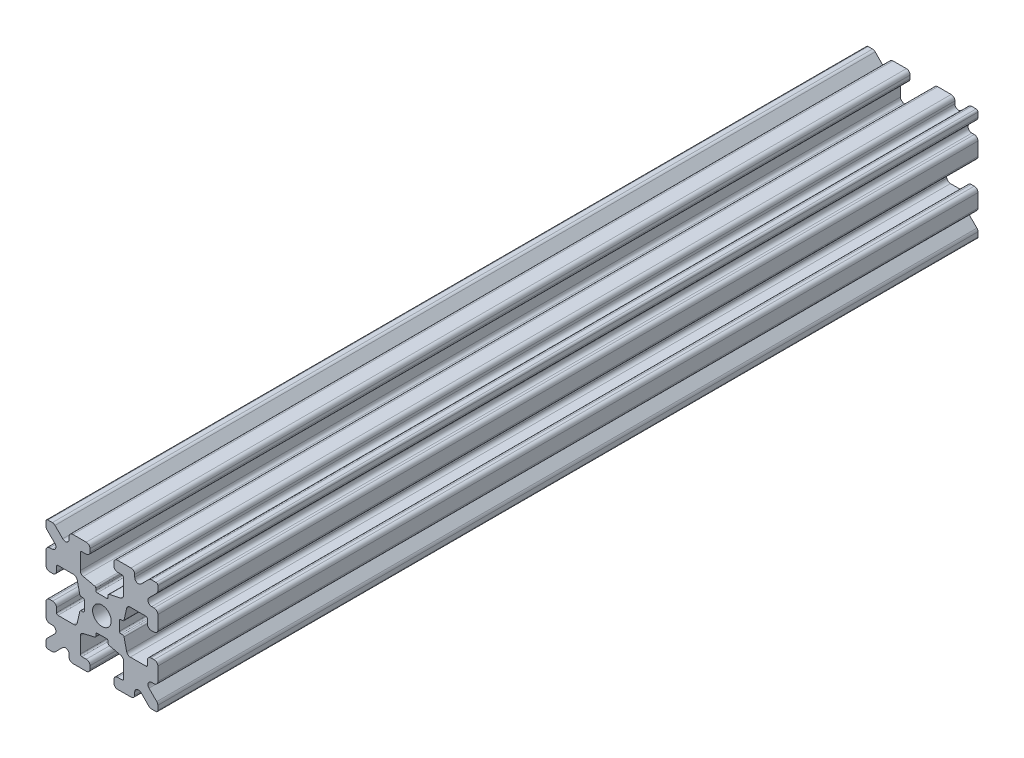
SolidWorks part; units mm, degrees
ref_plane "Front Plane" through (0, 0, 0) normal (0, 0, 1) x (1, 0, 0)
ref_plane "Top Plane" through (0, 0, 0) normal (0, 1, 0) x (1, 0, 0)
ref_plane "Right Plane" through (0, 0, 0) normal (1, 0, 0) x (0, 0, -1)
sketch "Sketch1" plane through (0, 0, 0) normal (0, 0, 1) x (1, 0, 0)
  line L1 (-7.5, -7.5) -> (7.5, -7.5)
  line L2 (-7.5, -7.5) -> (-7.5, 7.5)
  line L3 (-7.5, 7.5) -> (7.5, 7.5)
  line L4 (7.5, -7.5) -> (7.5, 7.5)
  line L5 (-7.5, -7.5) -> (7.5, 7.5) construction
  line L6 (-7.5, 7.5) -> (7.5, -7.5) construction
  circle A0 centre (0, 0) radius 1.25
  point P0 (0, 0)
  dimension "D2" = 2.5
  dimension "D1" = 15
extrude "Boss-Extrude1" add sketch "Sketch1" along normal mid plane 110
fillet "Fillet1" radius 0.25 4 edges at (7.5, -7.5, 0) (-7.5, -7.5, 0) (7.5, 7.5, 0) (-7.5, 7.5, 0)
sketch "Sketch2" plane through (0, 0, 55) normal (0, 0, 1) x (1, 0, 0)
  line L0 (-7.5, 7.25) -> (-7.5, -7.25) construction
  line L1 (-7.5, 1.6) -> (-6.1, 1.6)
  line L2 (-7.5, 1.6) -> (-7.5, -1.6)
  line L3 (-7.5, -1.6) -> (-6.1, -1.6)
  line L4 (-6.1, 1.6) -> (-6.1, 2.9)
  line L5 (0, 0) -> (-12.1036, 0) construction
  line L6 (-6.1, -2.9) -> (-3.4, -2.9)
  line L7 (0, 0) -> (-7.25, 7.25) construction
  line L8 (-6.1, 2.9) -> (-3.4, 2.9)
  line L9 (-3.4, -2.9) -> (-3.4, 2.9)
  line L10 (55, 0) -> (-55, 0) construction
  line L11 (-6.1, -2.9) -> (-6.1, -1.6)
  line L12 (2.9, 6.1) -> (1.6, 6.1)
  line L13 (2.9, 3.4) -> (-2.9, 3.4)
  line L14 (-2.9, 6.1) -> (-2.9, 3.4)
  line L15 (2.9, 6.1) -> (2.9, 3.4)
  line L16 (-1.6, 6.1) -> (-2.9, 6.1)
  line L17 (1.6, 7.5) -> (1.6, 6.1)
  line L18 (-1.6, 7.5) -> (1.6, 7.5)
  line L19 (-1.6, 7.5) -> (-1.6, 6.1)
  line L20 (-1.6, -7.5) -> (-1.6, -6.1)
  line L21 (-1.6, -7.5) -> (1.6, -7.5)
  line L22 (1.6, -7.5) -> (1.6, -6.1)
  line L23 (-1.6, -6.1) -> (-2.9, -6.1)
  line L24 (2.9, -6.1) -> (2.9, -3.4)
  line L25 (-2.9, -6.1) -> (-2.9, -3.4)
  line L26 (2.9, -3.4) -> (-2.9, -3.4)
  line L27 (2.9, -6.1) -> (1.6, -6.1)
  line L28 (6.1, -2.9) -> (6.1, -1.6)
  line L29 (3.4, -2.9) -> (3.4, 2.9)
  line L30 (6.1, 2.9) -> (3.4, 2.9)
  line L31 (6.1, -2.9) -> (3.4, -2.9)
  line L32 (6.1, 1.6) -> (6.1, 2.9)
  line L33 (7.5, -1.6) -> (6.1, -1.6)
  line L34 (7.5, 1.6) -> (7.5, -1.6)
  line L35 (7.5, 1.6) -> (6.1, 1.6)
  dimension "D1" = 3.2
  dimension "D2" = 5.8
  dimension "D3" = 1.4
  dimension "D4" = 2.7
extrude "Cut-Extrude1" cut sketch "Sketch2" against normal through all
sketch "Sketch4" plane through (0, 0, 55) normal (0, 0, 1) x (1, 0, 0)
  line L0 (-3.4, 2.9) -> (-2.75, 0)
  line L1 (55, 0) -> (-55, 0) construction
  line L2 (-2.75, 0) -> (-3.4, -2.9)
  line L3 (-3.4, -2.9) -> (-3.4, 2.9) construction
  line L4 (-3.4, 2.9) -> (-3.4, -2.9)
  line L5 (-2.9, 3.4) -> (0, 2.75)
  line L6 (0, 2.75) -> (2.9, 3.4)
  line L7 (2.9, 3.4) -> (-2.9, 3.4)
  line L8 (3.4, 2.9) -> (2.75, 0)
  line L9 (2.75, 0) -> (3.4, -2.9)
  line L10 (3.4, -2.9) -> (3.4, 2.9)
  line L11 (-2.9, -3.4) -> (0, -2.75)
  line L12 (0, -2.75) -> (2.9, -3.4)
  line L13 (2.9, -3.4) -> (-2.9, -3.4)
  circle A2 centre (0, 0) radius 2.75
  circle A3 centre (0, 0) radius 2.75 construction
  dimension "D1" = 1.5
extrude "Cut-Extrude3" cut sketch "Sketch4" against normal through all
fillet "Fillet3" radius 0.5 16 edges at (-6.1, -1.6, 0) (-7.5, -1.6, 0) (-6.1, 1.6, 0) (-7.5, 1.6, 0) (-1.6, -7.5, 0) (-1.6, -6.1, 0) (1.6, -7.5, 0) (1.6, -6.1, 0) (6.1, -1.6, 0) (7.5, -1.6, 0) (7.5, 1.6, 0) (6.1, 1.6, 0) (1.6, 7.5, 0) (1.6, 6.1, 0) (-1.6, 7.5, 0) (-1.6, 6.1, 0)
fillet "Fillet4" radius 0.5 8 edges at (-3.4, 2.9, 0) (-3.4, -2.9, 0) (2.9, -3.4, 0) (-2.9, -3.4, 0) (3.4, -2.9, 0) (3.4, 2.9, 0) (-2.9, 3.4, 0) (2.9, 3.4, 0)
fillet "Fillet5" radius 3 4 edges at (0, -2.75, 0) (2.75, 0, 0) (-2.75, 0, 0) (0, 2.75, 0)
fillet "Fillet6" radius 0.2 8 edges at (-2.9, -6.1, 0) (2.9, -6.1, 0) (6.1, -2.9, 0) (6.1, 2.9, 0) (2.9, 6.1, 0) (-2.9, 6.1, 0) (-6.1, -2.9, 0) (-6.1, 2.9, 0)
sketch "Sketch5" plane through (0, 0, 55) normal (0, 0, 1) x (1, 0, 0)
  line L0 (0, 0) -> (-7.25, 7.25) construction
  line L1 (-7.5, 6.4393) -> (-5.4607, 4.4)
  line L2 (-6.4393, 7.5) -> (-4.4, 5.4607)
  line L3 (-7.5, 4.4) -> (-5.4607, 4.4)
  line L4 (-3.8003, 2.9) -> (-5.9, 2.9) construction
  line L5 (0, 0) -> (-12.1819, 0) construction
  line L6 (-4.4, 7.5) -> (-4.4, 5.4607)
  line L7 (-2.9, 5.9) -> (-2.9, 3.8003) construction
  line L8 (-7.5, 6.4393) -> (-7.5, 4.4)
  line L9 (-7.5, 7.25) -> (-7.5, 2.1) construction
  line L10 (2.1, -7.5) -> (7.25, -7.5) construction
  line L11 (7.5, -7.25) -> (7.5, -2.1) construction
  line L12 (7.25, 7.5) -> (2.1, 7.5) construction
  line L13 (-2.1, 7.5) -> (-7.25, 7.5) construction
  line L14 (-4.4, 7.5) -> (-6.4393, 7.5)
  line L16 (55, 0) -> (-55, 0) construction
  line L17 (0, 0) -> (0, 10.993) construction
  line L18 (0, -54.6431) -> (0, 54.6431) construction
  line L20 (4.4, 7.5) -> (6.4393, 7.5)
  line L22 (7.5, 6.4393) -> (7.5, 4.4)
  line L23 (4.4, 7.5) -> (4.4, 5.4607)
  line L24 (7.5, 4.4) -> (5.4607, 4.4)
  line L25 (6.4393, 7.5) -> (4.4, 5.4607)
  line L26 (7.5, 6.4393) -> (5.4607, 4.4)
  line L27 (7.5, -6.4393) -> (5.4607, -4.4)
  line L28 (6.4393, -7.5) -> (4.4, -5.4607)
  line L29 (7.5, -4.4) -> (5.4607, -4.4)
  line L30 (4.4, -7.5) -> (4.4, -5.4607)
  line L31 (7.5, -6.4393) -> (7.5, -4.4)
  line L33 (4.4, -7.5) -> (6.4393, -7.5)
  line L36 (-4.4, -7.5) -> (-6.4393, -7.5)
  line L38 (-7.5, -6.4393) -> (-7.5, -4.4)
  line L39 (-4.4, -7.5) -> (-4.4, -5.4607)
  line L40 (-7.5, -4.4) -> (-5.4607, -4.4)
  line L41 (-6.4393, -7.5) -> (-4.4, -5.4607)
  line L42 (-7.5, -6.4393) -> (-5.4607, -4.4)
  dimension "D1" = 1.5
  dimension "D2" = 1.5
  dimension "D3" = 1.5
extrude "Cut-Extrude4" cut sketch "Sketch5" against normal through all
fillet "Fillet8" radius 0.5 24 edges at (-5.4607, 4.4, 0) (-7.5, 4.4, 0) (-5.4607, -4.4, 0) (-7.5, -4.4, 0) (-4.4, -7.5, 0) (-4.4, -5.4607, 0) (4.4, -7.5, 0) (4.4, -5.4607, 0) (5.4607, -4.4, 0) (7.5, -4.4, 0) (7.5, 4.4, 0) (5.4607, 4.4, 0) (4.4, 5.4607, 0) (4.4, 7.5, 0) (-4.4, 5.4607, 0) (-4.4, 7.5, 0) (-6.4393, 7.5, 0) (-7.5, 6.4393, 0) (6.4393, 7.5, 0) (7.5, 6.4393, 0) (6.4393, -7.5, 0) (7.5, -6.4393, 0) (-6.4393, -7.5, 0) (-7.5, -6.4393, 0)
sketch "Sketch6" plane through (0, 0, 55) normal (0, 0, 1) x (1, 0, 0)
  line L0 (0, 0) -> (0, 11.013) construction
  line L1 (0.6561, 2.8971) -> (2.1235, 2.8971) construction
  line L2 (0, -54.6431) -> (0, 54.6431) construction
  line L3 (0, 0) -> (7.25, 7.25) construction
  line L4 (7.5, 0.8255) -> (7.5, -0.8255)
  line L5 (2.3471, 0.8255) -> (7.5, 0.8255)
  line L6 (0, 0) -> (12.4016, 0) construction
  line L7 (0.8255, -7.5) -> (-0.8255, -7.5)
  line L8 (2.3471, -0.8255) -> (2.3471, 0.8255)
  line L9 (0.8255, -2.3471) -> (0.8255, -7.5)
  line L10 (7.5, -0.8255) -> (2.3471, -0.8255)
  line L11 (-7.5, -0.8255) -> (-2.3471, -0.8255)
  line L12 (-2.3471, -0.8255) -> (-2.3471, 0.8255)
  line L13 (-0.8255, -2.3471) -> (0.8255, -2.3471)
  line L14 (-0.8255, 7.5) -> (-0.8255, 2.3471)
  line L15 (-0.8255, 2.3471) -> (0.8255, 2.3471)
  line L16 (-0.8255, -7.5) -> (-0.8255, -2.3471)
  line L17 (0.8255, 2.3471) -> (0.8255, 7.5)
  line L18 (0.8255, 7.5) -> (-0.8255, 7.5)
  line L19 (3.9, 7.5) -> (2.1, 7.5) construction
  line L20 (-2.3471, 0.8255) -> (-7.5, 0.8255)
  line L21 (-7.5, 0.8255) -> (-7.5, -0.8255)
  point P5 (0, -2.5973)
  point P7 (0, 2.5973)
  dimension "D3" = 0.55
  dimension "D1" = 1.651
extrude "Cut-Extrude5" cut sketch "Sketch6" against normal through all
fillet "Fillet10" radius 0.2 16 edges at (-2.935, 0.8255, 0) (-2.935, -0.8255, 0) (2.935, -0.8255, 0) (2.935, 0.8255, 0) (0.8255, 2.935, 0) (-0.8255, 2.935, 0) (-2.3471, 0.8255, 0) (-2.3471, -0.8255, 0) (0.8255, 2.3471, 0) (-0.8255, 2.3471, 0) (2.3471, 0.8255, 0) (2.3471, -0.8255, 0) (0.8255, -2.935, 0) (0.8255, -2.3471, 0) (-0.8255, -2.3471, 0) (-0.8255, -2.935, 0)
